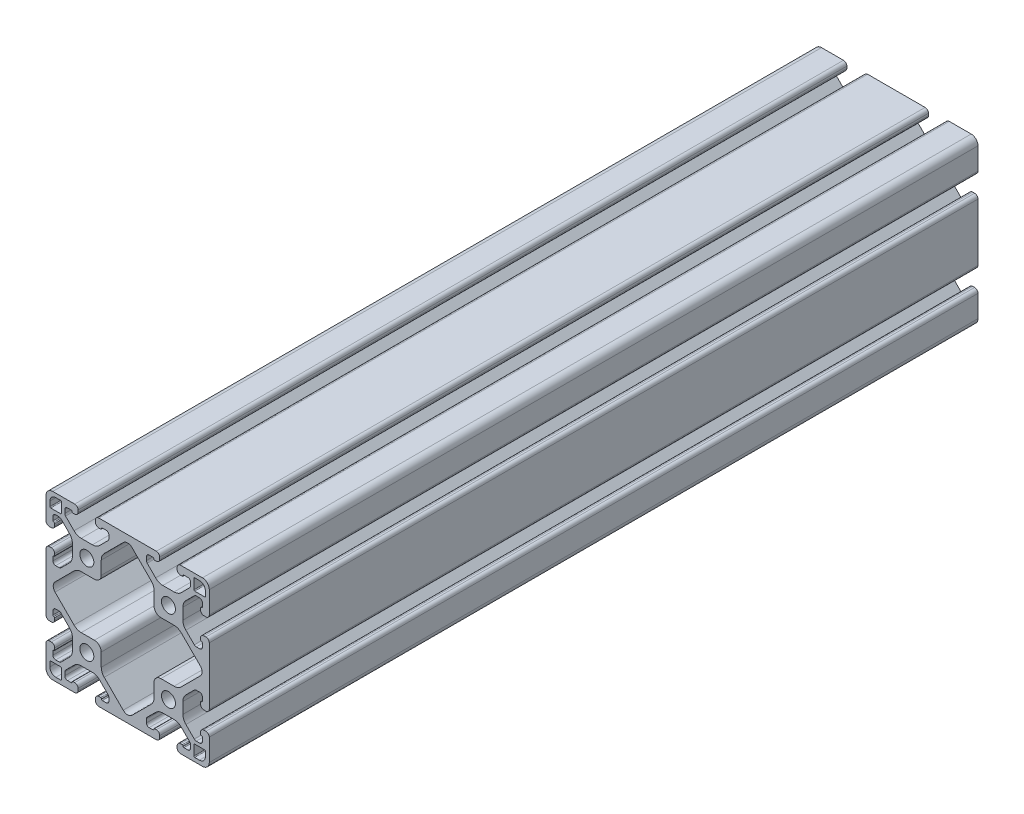
SolidWorks part; units mm, degrees
material "6061 Alloy"
ref_plane "Front Plane" through (0, 0, 0) normal (0, 0, 1) x (1, 0, 0)
ref_plane "Top Plane" through (0, 0, 0) normal (0, 1, 0) x (1, 0, 0)
ref_plane "Right Plane" through (0, 0, 0) normal (1, 0, 0) x (0, 0, -1)
sketch "Sketch1" plane through (0, 0, 0) normal (0, 0, 1) x (1, 0, 0)
  line L0 (33.8793, 2.0655) -> (25.0169, 10.9278)
  line L1 (25.0169, -10.9278) -> (33.8793, -2.0655)
  line L2 (15.494, -12.319) -> (21.6583, -12.319)
  line L3 (12.319, -21.6583) -> (12.319, -15.494)
  line L4 (2.0655, -33.8793) -> (10.9278, -25.0169)
  line L5 (-10.9278, -25.0169) -> (-2.0655, -33.8793)
  line L6 (-12.319, -15.494) -> (-12.319, -21.6583)
  line L7 (-21.6583, -12.319) -> (-15.494, -12.319)
  line L8 (-33.8793, -2.0655) -> (-25.0169, -10.9278)
  line L9 (-25.0169, 10.9278) -> (-33.8793, 2.0655)
  line L10 (-15.494, 12.319) -> (-21.6583, 12.319)
  line L11 (-12.319, 21.6583) -> (-12.319, 15.494)
  line L12 (-2.0655, 33.8793) -> (-10.9278, 25.0169)
  line L13 (10.9278, 25.0169) -> (2.0655, 33.8793)
  line L14 (12.319, 15.494) -> (12.319, 21.6583)
  line L15 (21.6583, 12.319) -> (15.494, 12.319)
  line L16 (-16.4102, 23.2956) -> (-17.6936, 22.0229) construction
  line L17 (-16.0771, 20.4064) -> (-14.8044, 21.6898) construction
  line L18 (-14.7067, 16.3231) -> (-16.0771, 17.6936) construction
  line L19 (-17.6936, 16.0771) -> (-16.3231, 14.7067) construction
  line L20 (-21.7769, 14.7067) -> (-20.4064, 16.0771) construction
  line L21 (-22.0229, 17.6936) -> (-23.3933, 16.3231) construction
  line L22 (-23.3933, 21.7769) -> (-22.0229, 20.4064) construction
  line L23 (-20.4064, 22.0229) -> (-21.7769, 23.3933) construction
  line L24 (14.8044, 21.6898) -> (16.0771, 20.4064) construction
  line L25 (17.6936, 22.0229) -> (16.4102, 23.2956) construction
  line L26 (21.7769, 23.3933) -> (20.4064, 22.0229) construction
  line L27 (22.0229, 20.4064) -> (23.3933, 21.7769) construction
  line L28 (23.3933, 16.3231) -> (22.0229, 17.6936) construction
  line L29 (20.4064, 16.0771) -> (21.7769, 14.7067) construction
  line L30 (16.3231, 14.7067) -> (17.6936, 16.0771) construction
  line L31 (16.0771, 17.6936) -> (14.7067, 16.3231) construction
  line L32 (16.4102, -23.2956) -> (17.6936, -22.0229) construction
  line L33 (16.0771, -20.4064) -> (14.8044, -21.6898) construction
  line L34 (14.7067, -16.3231) -> (16.0771, -17.6936) construction
  line L35 (17.6936, -16.0771) -> (16.3231, -14.7067) construction
  line L36 (21.7769, -14.7067) -> (20.4064, -16.0771) construction
  line L37 (22.0229, -17.6936) -> (23.3933, -16.3231) construction
  line L38 (23.3933, -21.7769) -> (22.0229, -20.4064) construction
  line L39 (20.4064, -22.0229) -> (21.7769, -23.3933) construction
  line L40 (-14.8044, -21.6898) -> (-16.0771, -20.4064) construction
  line L41 (-17.6936, -22.0229) -> (-16.4102, -23.2956) construction
  line L42 (-21.7769, -23.3933) -> (-20.4064, -22.0229) construction
  line L43 (-22.0229, -20.4064) -> (-23.3933, -21.7769) construction
  line L44 (-23.3933, -16.3231) -> (-22.0229, -17.6936) construction
  line L45 (-20.4064, -16.0771) -> (-21.7769, -14.7067) construction
  line L46 (-16.3231, -14.7067) -> (-17.6936, -16.0771) construction
  line L47 (-16.0771, -17.6936) -> (-14.7067, -16.3231) construction
  line L48 (34.417, -25.908) -> (34.4932, -25.908)
  line L49 (34.8742, -26.289) -> (34.8742, -28.067)
  line L50 (33.6042, -29.337) -> (32.0183, -29.337)
  line L51 (31.1203, -28.965) -> (27.1722, -25.0169)
  line L52 (25.781, -21.6583) -> (25.781, -16.4417)
  line L53 (27.1722, -13.0831) -> (31.1203, -9.135)
  line L54 (32.0183, -8.763) -> (33.6042, -8.763)
  line L55 (34.8742, -10.033) -> (34.8742, -11.811)
  line L56 (34.4932, -12.192) -> (34.417, -12.192)
  line L57 (34.036, -12.573) -> (34.036, -13.4112)
  line L58 (35.6108, -14.986) -> (36.5252, -14.986)
  line L59 (38.1, -13.4112) -> (38.1, 13.4112)
  line L60 (36.5252, 14.986) -> (35.6108, 14.986)
  line L61 (34.036, 13.4112) -> (34.036, 12.573)
  line L62 (34.417, 12.192) -> (34.4932, 12.192)
  line L63 (34.8742, 11.811) -> (34.8742, 10.033)
  line L64 (33.6042, 8.763) -> (32.0183, 8.763)
  line L65 (31.1203, 9.135) -> (27.1722, 13.0831)
  line L66 (25.781, 16.4417) -> (25.781, 21.6583)
  line L67 (27.1722, 25.0169) -> (31.1203, 28.965)
  line L68 (32.0183, 29.337) -> (33.6042, 29.337)
  line L69 (34.8742, 28.067) -> (34.8742, 26.289)
  line L70 (34.4932, 25.908) -> (34.417, 25.908)
  line L71 (34.036, 25.527) -> (34.036, 24.6888)
  line L72 (35.6108, 23.114) -> (36.5252, 23.114)
  line L73 (38.1, 24.6888) -> (38.1, 34.925)
  line L74 (34.925, 38.1) -> (24.6888, 38.1)
  line L75 (23.114, 36.5252) -> (23.114, 35.6108)
  line L76 (24.6888, 34.036) -> (25.527, 34.036)
  line L77 (25.908, 34.417) -> (25.908, 34.4932)
  line L78 (26.289, 34.8742) -> (28.067, 34.8742)
  line L79 (29.337, 33.6042) -> (29.337, 32.0183)
  line L80 (28.965, 31.1203) -> (25.0169, 27.1722)
  line L81 (21.6583, 25.781) -> (16.4417, 25.781)
  line L82 (13.0831, 27.1722) -> (9.135, 31.1203)
  line L83 (8.763, 32.0183) -> (8.763, 33.6042)
  line L84 (10.033, 34.8742) -> (11.811, 34.8742)
  line L85 (12.192, 34.4932) -> (12.192, 34.417)
  line L86 (12.573, 34.036) -> (13.4112, 34.036)
  line L87 (14.986, 35.6108) -> (14.986, 36.5252)
  line L88 (13.4112, 38.1) -> (-13.4112, 38.1)
  line L89 (-14.986, 36.5252) -> (-14.986, 35.6108)
  line L90 (-13.4112, 34.036) -> (-12.573, 34.036)
  line L91 (-12.192, 34.417) -> (-12.192, 34.4932)
  line L92 (-11.811, 34.8742) -> (-10.033, 34.8742)
  line L93 (-8.763, 33.6042) -> (-8.763, 32.0183)
  line L94 (-9.135, 31.1203) -> (-13.0831, 27.1722)
  line L95 (-16.4417, 25.781) -> (-21.6583, 25.781)
  line L96 (-25.0169, 27.1722) -> (-28.965, 31.1203)
  line L97 (-29.337, 32.0183) -> (-29.337, 33.6042)
  line L98 (-28.067, 34.8742) -> (-26.289, 34.8742)
  line L99 (-25.908, 34.4932) -> (-25.908, 34.417)
  line L100 (-25.527, 34.036) -> (-24.6888, 34.036)
  line L101 (-23.114, 35.6108) -> (-23.114, 36.5252)
  line L102 (-24.6888, 38.1) -> (-34.925, 38.1)
  line L103 (-38.1, 34.925) -> (-38.1, 24.6888)
  line L104 (-36.5252, 23.114) -> (-35.6108, 23.114)
  line L105 (-34.036, 24.6888) -> (-34.036, 25.527)
  line L106 (-34.417, 25.908) -> (-34.4932, 25.908)
  line L107 (-34.8742, 26.289) -> (-34.8742, 28.067)
  line L108 (-33.6042, 29.337) -> (-32.0183, 29.337)
  line L109 (-31.1203, 28.965) -> (-27.1722, 25.0169)
  line L110 (-25.781, 21.6583) -> (-25.781, 16.4417)
  line L111 (-27.1722, 13.0831) -> (-31.1203, 9.135)
  line L112 (-32.0183, 8.763) -> (-33.6042, 8.763)
  line L113 (-34.8742, 10.033) -> (-34.8742, 11.811)
  line L114 (-34.4932, 12.192) -> (-34.417, 12.192)
  line L115 (-34.036, 12.573) -> (-34.036, 13.4112)
  line L116 (-35.6108, 14.986) -> (-36.5252, 14.986)
  line L117 (-38.1, 13.4112) -> (-38.1, -13.4112)
  line L118 (-36.5252, -14.986) -> (-35.6108, -14.986)
  line L119 (-34.036, -13.4112) -> (-34.036, -12.573)
  line L120 (-34.417, -12.192) -> (-34.4932, -12.192)
  line L121 (-34.8742, -11.811) -> (-34.8742, -10.033)
  line L122 (-33.6042, -8.763) -> (-32.0183, -8.763)
  line L123 (-31.1203, -9.135) -> (-27.1722, -13.0831)
  line L124 (-25.781, -16.4417) -> (-25.781, -21.6583)
  line L125 (-27.1722, -25.0169) -> (-31.1203, -28.965)
  line L126 (-32.0183, -29.337) -> (-33.6042, -29.337)
  line L127 (-34.8742, -28.067) -> (-34.8742, -26.289)
  line L128 (-34.4932, -25.908) -> (-34.417, -25.908)
  line L129 (-34.036, -25.527) -> (-34.036, -24.6888)
  line L130 (-35.6108, -23.114) -> (-36.5252, -23.114)
  line L131 (-38.1, -24.6888) -> (-38.1, -34.925)
  line L132 (-34.925, -38.1) -> (-24.6888, -38.1)
  line L133 (-23.114, -36.5252) -> (-23.114, -35.6108)
  line L134 (-24.6888, -34.036) -> (-25.527, -34.036)
  line L135 (-25.908, -34.417) -> (-25.908, -34.4932)
  line L136 (-26.289, -34.8742) -> (-28.067, -34.8742)
  line L137 (-29.337, -33.6042) -> (-29.337, -32.0183)
  line L138 (-28.965, -31.1203) -> (-25.0169, -27.1722)
  line L139 (-21.6583, -25.781) -> (-16.4417, -25.781)
  line L140 (-13.0831, -27.1722) -> (-9.135, -31.1203)
  line L141 (-8.763, -32.0183) -> (-8.763, -33.6042)
  line L142 (-10.033, -34.8742) -> (-11.811, -34.8742)
  line L143 (-12.192, -34.4932) -> (-12.192, -34.417)
  line L144 (-12.573, -34.036) -> (-13.4112, -34.036)
  line L145 (-14.986, -35.6108) -> (-14.986, -36.5252)
  line L146 (-13.4112, -38.1) -> (13.4112, -38.1)
  line L147 (14.986, -36.5252) -> (14.986, -35.6108)
  line L148 (13.4112, -34.036) -> (12.573, -34.036)
  line L149 (12.192, -34.417) -> (12.192, -34.4932)
  line L150 (11.811, -34.8742) -> (10.033, -34.8742)
  line L151 (8.763, -33.6042) -> (8.763, -32.0183)
  line L152 (9.135, -31.1203) -> (13.0831, -27.1722)
  line L153 (16.4417, -25.781) -> (21.6583, -25.781)
  line L154 (25.0169, -27.1722) -> (28.965, -31.1203)
  line L155 (29.337, -32.0183) -> (29.337, -33.6042)
  line L156 (28.067, -34.8742) -> (26.289, -34.8742)
  line L157 (25.908, -34.4932) -> (25.908, -34.417)
  line L158 (25.527, -34.036) -> (24.6888, -34.036)
  line L159 (23.114, -35.6108) -> (23.114, -36.5252)
  line L160 (24.6888, -38.1) -> (34.925, -38.1)
  line L161 (38.1, -34.925) -> (38.1, -24.6888)
  line L162 (36.5252, -23.114) -> (35.6108, -23.114)
  line L163 (34.036, -24.6888) -> (34.036, -25.527)
  line L164 (-31.2928, 36.2966) -> (-33.5026, 36.2966)
  line L165 (-30.9118, 31.2928) -> (-30.9118, 35.9156)
  line L166 (-35.9156, 30.9118) -> (-31.2928, 30.9118)
  line L167 (-36.2966, 33.5026) -> (-36.2966, 31.2928)
  line L168 (30.9118, 35.9156) -> (30.9118, 31.2928)
  line L169 (33.5026, 36.2966) -> (31.2928, 36.2966)
  line L170 (36.2966, 31.2928) -> (36.2966, 33.5026)
  line L171 (31.2928, 30.9118) -> (35.9156, 30.9118)
  line L172 (31.2928, -36.2966) -> (33.5026, -36.2966)
  line L173 (30.9118, -31.2928) -> (30.9118, -35.9156)
  line L174 (35.9156, -30.9118) -> (31.2928, -30.9118)
  line L175 (36.2966, -33.5026) -> (36.2966, -31.2928)
  line L176 (-30.9118, -35.9156) -> (-30.9118, -31.2928)
  line L177 (-33.5026, -36.2966) -> (-31.2928, -36.2966)
  line L178 (-36.2966, -31.2928) -> (-36.2966, -33.5026)
  line L179 (-31.2928, -30.9118) -> (-35.9156, -30.9118)
  arc A0 (33.8793, -2.0655) -> (33.8793, 2.0655) centre (31.8138, 0) ccw
  arc A1 (21.6583, -12.319) -> (25.0169, -10.9278) centre (21.6583, -7.5692) ccw
  arc A2 (15.494, -12.319) -> (12.319, -15.494) centre (15.494, -15.494) ccw
  arc A3 (10.9278, -25.0169) -> (12.319, -21.6583) centre (7.5692, -21.6583) ccw
  arc A4 (-2.0655, -33.8793) -> (2.0655, -33.8793) centre (0, -31.8138) ccw
  arc A5 (-12.319, -21.6583) -> (-10.9278, -25.0169) centre (-7.5692, -21.6583) ccw
  arc A6 (-12.319, -15.494) -> (-15.494, -12.319) centre (-15.494, -15.494) ccw
  arc A7 (-25.0169, -10.9278) -> (-21.6583, -12.319) centre (-21.6583, -7.5692) ccw
  arc A8 (-33.8793, 2.0655) -> (-33.8793, -2.0655) centre (-31.8138, 0) ccw
  arc A9 (-21.6583, 12.319) -> (-25.0169, 10.9278) centre (-21.6583, 7.5692) ccw
  arc A10 (-15.494, 12.319) -> (-12.319, 15.494) centre (-15.494, 15.494) ccw
  arc A11 (-10.9278, 25.0169) -> (-12.319, 21.6583) centre (-7.5692, 21.6583) ccw
  arc A12 (2.0655, 33.8793) -> (-2.0655, 33.8793) centre (0, 31.8138) ccw
  arc A13 (12.319, 21.6583) -> (10.9278, 25.0169) centre (7.5692, 21.6583) ccw
  arc A14 (12.319, 15.494) -> (15.494, 12.319) centre (15.494, 15.494) ccw
  arc A15 (25.0169, 10.9278) -> (21.6583, 12.319) centre (21.6583, 7.5692) ccw
  arc A16 (-14.8044, 21.6898) -> (-16.4102, 23.2956) centre (-15.5149, 22.5851) ccw construction
  arc A17 (-16.0771, 17.6936) -> (-16.0771, 20.4064) centre (-19.05, 19.05) ccw construction
  arc A18 (-16.3231, 14.7067) -> (-14.7067, 16.3231) centre (-15.5149, 15.5149) ccw construction
  arc A19 (-20.4064, 16.0771) -> (-17.6936, 16.0771) centre (-19.05, 19.05) ccw construction
  arc A20 (-23.3933, 16.3231) -> (-21.7769, 14.7067) centre (-22.5851, 15.5149) ccw construction
  arc A21 (-22.0229, 20.4064) -> (-22.0229, 17.6936) centre (-19.05, 19.05) ccw construction
  arc A22 (-21.7769, 23.3933) -> (-23.3933, 21.7769) centre (-22.5851, 22.5851) ccw construction
  arc A23 (-17.6936, 22.0229) -> (-20.4064, 22.0229) centre (-19.05, 19.05) ccw construction
  arc A24 (16.0771, 20.4064) -> (16.0771, 17.6936) centre (19.05, 19.05) ccw construction
  arc A25 (16.4102, 23.2956) -> (14.8044, 21.6898) centre (15.5149, 22.5851) ccw construction
  arc A26 (20.4064, 22.0229) -> (17.6936, 22.0229) centre (19.05, 19.05) ccw construction
  arc A27 (23.3933, 21.7769) -> (21.7769, 23.3933) centre (22.5851, 22.5851) ccw construction
  arc A28 (22.0229, 17.6936) -> (22.0229, 20.4064) centre (19.05, 19.05) ccw construction
  arc A29 (21.7769, 14.7067) -> (23.3933, 16.3231) centre (22.5851, 15.5149) ccw construction
  arc A30 (17.6936, 16.0771) -> (20.4064, 16.0771) centre (19.05, 19.05) ccw construction
  arc A31 (14.7067, 16.3231) -> (16.3231, 14.7067) centre (15.5149, 15.5149) ccw construction
  arc A32 (17.6936, -22.0229) -> (20.4064, -22.0229) centre (19.05, -19.05) ccw construction
  arc A33 (14.8044, -21.6898) -> (16.4102, -23.2956) centre (15.5149, -22.5851) ccw construction
  arc A34 (16.0771, -17.6936) -> (16.0771, -20.4064) centre (19.05, -19.05) ccw construction
  arc A35 (16.3231, -14.7067) -> (14.7067, -16.3231) centre (15.5149, -15.5149) ccw construction
  arc A36 (20.4064, -16.0771) -> (17.6936, -16.0771) centre (19.05, -19.05) ccw construction
  arc A37 (23.3933, -16.3231) -> (21.7769, -14.7067) centre (22.5851, -15.5149) ccw construction
  arc A38 (22.0229, -20.4064) -> (22.0229, -17.6936) centre (19.05, -19.05) ccw construction
  arc A39 (21.7769, -23.3933) -> (23.3933, -21.7769) centre (22.5851, -22.5851) ccw construction
  arc A40 (-16.4102, -23.2956) -> (-14.8044, -21.6898) centre (-15.5149, -22.5851) ccw construction
  arc A41 (-20.4064, -22.0229) -> (-17.6936, -22.0229) centre (-19.05, -19.05) ccw construction
  arc A42 (-23.3933, -21.7769) -> (-21.7769, -23.3933) centre (-22.5851, -22.5851) ccw construction
  arc A43 (-22.0229, -17.6936) -> (-22.0229, -20.4064) centre (-19.05, -19.05) ccw construction
  arc A44 (-21.7769, -14.7067) -> (-23.3933, -16.3231) centre (-22.5851, -15.5149) ccw construction
  arc A45 (-17.6936, -16.0771) -> (-20.4064, -16.0771) centre (-19.05, -19.05) ccw construction
  arc A46 (-14.7067, -16.3231) -> (-16.3231, -14.7067) centre (-15.5149, -15.5149) ccw construction
  arc A47 (-16.0771, -20.4064) -> (-16.0771, -17.6936) centre (-19.05, -19.05) ccw construction
  arc A48 (34.036, -25.527) -> (34.417, -25.908) centre (34.417, -25.527) ccw
  arc A49 (34.8742, -26.289) -> (34.4932, -25.908) centre (34.4932, -26.289) ccw
  arc A50 (33.6042, -29.337) -> (34.8742, -28.067) centre (33.6042, -28.067) ccw
  arc A51 (31.1203, -28.965) -> (32.0183, -29.337) centre (32.0183, -28.067) ccw
  arc A52 (25.781, -21.6583) -> (27.1722, -25.0169) centre (30.5308, -21.6583) ccw
  arc A53 (27.1722, -13.0831) -> (25.781, -16.4417) centre (30.5308, -16.4417) ccw
  arc A54 (32.0183, -8.763) -> (31.1203, -9.135) centre (32.0183, -10.033) ccw
  arc A55 (34.8742, -10.033) -> (33.6042, -8.763) centre (33.6042, -10.033) ccw
  arc A56 (34.4932, -12.192) -> (34.8742, -11.811) centre (34.4932, -11.811) ccw
  arc A57 (34.417, -12.192) -> (34.036, -12.573) centre (34.417, -12.573) ccw
  arc A58 (34.036, -13.4112) -> (35.6108, -14.986) centre (35.6108, -13.4112) ccw
  arc A59 (36.5252, -14.986) -> (38.1, -13.4112) centre (36.5252, -13.4112) ccw
  arc A60 (38.1, 13.4112) -> (36.5252, 14.986) centre (36.5252, 13.4112) ccw
  arc A61 (35.6108, 14.986) -> (34.036, 13.4112) centre (35.6108, 13.4112) ccw
  arc A62 (34.036, 12.573) -> (34.417, 12.192) centre (34.417, 12.573) ccw
  arc A63 (34.8742, 11.811) -> (34.4932, 12.192) centre (34.4932, 11.811) ccw
  arc A64 (33.6042, 8.763) -> (34.8742, 10.033) centre (33.6042, 10.033) ccw
  arc A65 (31.1203, 9.135) -> (32.0183, 8.763) centre (32.0183, 10.033) ccw
  arc A66 (25.781, 16.4417) -> (27.1722, 13.0831) centre (30.5308, 16.4417) ccw
  arc A67 (27.1722, 25.0169) -> (25.781, 21.6583) centre (30.5308, 21.6583) ccw
  arc A68 (32.0183, 29.337) -> (31.1203, 28.965) centre (32.0183, 28.067) ccw
  arc A69 (34.8742, 28.067) -> (33.6042, 29.337) centre (33.6042, 28.067) ccw
  arc A70 (34.4932, 25.908) -> (34.8742, 26.289) centre (34.4932, 26.289) ccw
  arc A71 (34.417, 25.908) -> (34.036, 25.527) centre (34.417, 25.527) ccw
  arc A72 (34.036, 24.6888) -> (35.6108, 23.114) centre (35.6108, 24.6888) ccw
  arc A73 (36.5252, 23.114) -> (38.1, 24.6888) centre (36.5252, 24.6888) ccw
  arc A74 (38.1, 34.925) -> (34.925, 38.1) centre (34.925, 34.925) ccw
  arc A75 (24.6888, 38.1) -> (23.114, 36.5252) centre (24.6888, 36.5252) ccw
  arc A76 (23.114, 35.6108) -> (24.6888, 34.036) centre (24.6888, 35.6108) ccw
  arc A77 (25.527, 34.036) -> (25.908, 34.417) centre (25.527, 34.417) ccw
  arc A78 (26.289, 34.8742) -> (25.908, 34.4932) centre (26.289, 34.4932) ccw
  arc A79 (29.337, 33.6042) -> (28.067, 34.8742) centre (28.067, 33.6042) ccw
  arc A80 (28.965, 31.1203) -> (29.337, 32.0183) centre (28.067, 32.0183) ccw
  arc A81 (21.6583, 25.781) -> (25.0169, 27.1722) centre (21.6583, 30.5308) ccw
  arc A82 (13.0831, 27.1722) -> (16.4417, 25.781) centre (16.4417, 30.5308) ccw
  arc A83 (8.763, 32.0183) -> (9.135, 31.1203) centre (10.033, 32.0183) ccw
  arc A84 (10.033, 34.8742) -> (8.763, 33.6042) centre (10.033, 33.6042) ccw
  arc A85 (12.192, 34.4932) -> (11.811, 34.8742) centre (11.811, 34.4932) ccw
  arc A86 (12.192, 34.417) -> (12.573, 34.036) centre (12.573, 34.417) ccw
  arc A87 (13.4112, 34.036) -> (14.986, 35.6108) centre (13.4112, 35.6108) ccw
  arc A88 (14.986, 36.5252) -> (13.4112, 38.1) centre (13.4112, 36.5252) ccw
  arc A89 (-13.4112, 38.1) -> (-14.986, 36.5252) centre (-13.4112, 36.5252) ccw
  arc A90 (-14.986, 35.6108) -> (-13.4112, 34.036) centre (-13.4112, 35.6108) ccw
  arc A91 (-12.573, 34.036) -> (-12.192, 34.417) centre (-12.573, 34.417) ccw
  arc A92 (-11.811, 34.8742) -> (-12.192, 34.4932) centre (-11.811, 34.4932) ccw
  arc A93 (-8.763, 33.6042) -> (-10.033, 34.8742) centre (-10.033, 33.6042) ccw
  arc A94 (-9.135, 31.1203) -> (-8.763, 32.0183) centre (-10.033, 32.0183) ccw
  arc A95 (-16.4417, 25.781) -> (-13.0831, 27.1722) centre (-16.4417, 30.5308) ccw
  arc A96 (-25.0169, 27.1722) -> (-21.6583, 25.781) centre (-21.6583, 30.5308) ccw
  arc A97 (-29.337, 32.0183) -> (-28.965, 31.1203) centre (-28.067, 32.0183) ccw
  arc A98 (-28.067, 34.8742) -> (-29.337, 33.6042) centre (-28.067, 33.6042) ccw
  arc A99 (-25.908, 34.4932) -> (-26.289, 34.8742) centre (-26.289, 34.4932) ccw
  arc A100 (-25.908, 34.417) -> (-25.527, 34.036) centre (-25.527, 34.417) ccw
  arc A101 (-24.6888, 34.036) -> (-23.114, 35.6108) centre (-24.6888, 35.6108) ccw
  arc A102 (-23.114, 36.5252) -> (-24.6888, 38.1) centre (-24.6888, 36.5252) ccw
  arc A103 (-34.925, 38.1) -> (-38.1, 34.925) centre (-34.925, 34.925) ccw
  arc A104 (-38.1, 24.6888) -> (-36.5252, 23.114) centre (-36.5252, 24.6888) ccw
  arc A105 (-35.6108, 23.114) -> (-34.036, 24.6888) centre (-35.6108, 24.6888) ccw
  arc A106 (-34.036, 25.527) -> (-34.417, 25.908) centre (-34.417, 25.527) ccw
  arc A107 (-34.8742, 26.289) -> (-34.4932, 25.908) centre (-34.4932, 26.289) ccw
  arc A108 (-33.6042, 29.337) -> (-34.8742, 28.067) centre (-33.6042, 28.067) ccw
  arc A109 (-31.1203, 28.965) -> (-32.0183, 29.337) centre (-32.0183, 28.067) ccw
  arc A110 (-25.781, 21.6583) -> (-27.1722, 25.0169) centre (-30.5308, 21.6583) ccw
  arc A111 (-27.1722, 13.0831) -> (-25.781, 16.4417) centre (-30.5308, 16.4417) ccw
  arc A112 (-32.0183, 8.763) -> (-31.1203, 9.135) centre (-32.0183, 10.033) ccw
  arc A113 (-34.8742, 10.033) -> (-33.6042, 8.763) centre (-33.6042, 10.033) ccw
  arc A114 (-34.4932, 12.192) -> (-34.8742, 11.811) centre (-34.4932, 11.811) ccw
  arc A115 (-34.417, 12.192) -> (-34.036, 12.573) centre (-34.417, 12.573) ccw
  arc A116 (-34.036, 13.4112) -> (-35.6108, 14.986) centre (-35.6108, 13.4112) ccw
  arc A117 (-36.5252, 14.986) -> (-38.1, 13.4112) centre (-36.5252, 13.4112) ccw
  arc A118 (-38.1, -13.4112) -> (-36.5252, -14.986) centre (-36.5252, -13.4112) ccw
  arc A119 (-35.6108, -14.986) -> (-34.036, -13.4112) centre (-35.6108, -13.4112) ccw
  arc A120 (-34.036, -12.573) -> (-34.417, -12.192) centre (-34.417, -12.573) ccw
  arc A121 (-34.8742, -11.811) -> (-34.4932, -12.192) centre (-34.4932, -11.811) ccw
  arc A122 (-33.6042, -8.763) -> (-34.8742, -10.033) centre (-33.6042, -10.033) ccw
  arc A123 (-31.1203, -9.135) -> (-32.0183, -8.763) centre (-32.0183, -10.033) ccw
  arc A124 (-25.781, -16.4417) -> (-27.1722, -13.0831) centre (-30.5308, -16.4417) ccw
  arc A125 (-27.1722, -25.0169) -> (-25.781, -21.6583) centre (-30.5308, -21.6583) ccw
  arc A126 (-32.0183, -29.337) -> (-31.1203, -28.965) centre (-32.0183, -28.067) ccw
  arc A127 (-34.8742, -28.067) -> (-33.6042, -29.337) centre (-33.6042, -28.067) ccw
  arc A128 (-34.4932, -25.908) -> (-34.8742, -26.289) centre (-34.4932, -26.289) ccw
  arc A129 (-34.417, -25.908) -> (-34.036, -25.527) centre (-34.417, -25.527) ccw
  arc A130 (-34.036, -24.6888) -> (-35.6108, -23.114) centre (-35.6108, -24.6888) ccw
  arc A131 (-36.5252, -23.114) -> (-38.1, -24.6888) centre (-36.5252, -24.6888) ccw
  arc A132 (-38.1, -34.925) -> (-34.925, -38.1) centre (-34.925, -34.925) ccw
  arc A133 (-24.6888, -38.1) -> (-23.114, -36.5252) centre (-24.6888, -36.5252) ccw
  arc A134 (-23.114, -35.6108) -> (-24.6888, -34.036) centre (-24.6888, -35.6108) ccw
  arc A135 (-25.527, -34.036) -> (-25.908, -34.417) centre (-25.527, -34.417) ccw
  arc A136 (-26.289, -34.8742) -> (-25.908, -34.4932) centre (-26.289, -34.4932) ccw
  arc A137 (-29.337, -33.6042) -> (-28.067, -34.8742) centre (-28.067, -33.6042) ccw
  arc A138 (-28.965, -31.1203) -> (-29.337, -32.0183) centre (-28.067, -32.0183) ccw
  arc A139 (-21.6583, -25.781) -> (-25.0169, -27.1722) centre (-21.6583, -30.5308) ccw
  arc A140 (-13.0831, -27.1722) -> (-16.4417, -25.781) centre (-16.4417, -30.5308) ccw
  arc A141 (-8.763, -32.0183) -> (-9.135, -31.1203) centre (-10.033, -32.0183) ccw
  arc A142 (-10.033, -34.8742) -> (-8.763, -33.6042) centre (-10.033, -33.6042) ccw
  arc A143 (-12.192, -34.4932) -> (-11.811, -34.8742) centre (-11.811, -34.4932) ccw
  arc A144 (-12.192, -34.417) -> (-12.573, -34.036) centre (-12.573, -34.417) ccw
  arc A145 (-13.4112, -34.036) -> (-14.986, -35.6108) centre (-13.4112, -35.6108) ccw
  arc A146 (-14.986, -36.5252) -> (-13.4112, -38.1) centre (-13.4112, -36.5252) ccw
  arc A147 (13.4112, -38.1) -> (14.986, -36.5252) centre (13.4112, -36.5252) ccw
  arc A148 (14.986, -35.6108) -> (13.4112, -34.036) centre (13.4112, -35.6108) ccw
  arc A149 (12.573, -34.036) -> (12.192, -34.417) centre (12.573, -34.417) ccw
  arc A150 (11.811, -34.8742) -> (12.192, -34.4932) centre (11.811, -34.4932) ccw
  arc A151 (8.763, -33.6042) -> (10.033, -34.8742) centre (10.033, -33.6042) ccw
  arc A152 (9.135, -31.1203) -> (8.763, -32.0183) centre (10.033, -32.0183) ccw
  arc A153 (16.4417, -25.781) -> (13.0831, -27.1722) centre (16.4417, -30.5308) ccw
  arc A154 (25.0169, -27.1722) -> (21.6583, -25.781) centre (21.6583, -30.5308) ccw
  arc A155 (29.337, -32.0183) -> (28.965, -31.1203) centre (28.067, -32.0183) ccw
  arc A156 (28.067, -34.8742) -> (29.337, -33.6042) centre (28.067, -33.6042) ccw
  arc A157 (25.908, -34.4932) -> (26.289, -34.8742) centre (26.289, -34.4932) ccw
  arc A158 (25.908, -34.417) -> (25.527, -34.036) centre (25.527, -34.417) ccw
  arc A159 (24.6888, -34.036) -> (23.114, -35.6108) centre (24.6888, -35.6108) ccw
  arc A160 (23.114, -36.5252) -> (24.6888, -38.1) centre (24.6888, -36.5252) ccw
  arc A161 (34.925, -38.1) -> (38.1, -34.925) centre (34.925, -34.925) ccw
  arc A162 (38.1, -24.6888) -> (36.5252, -23.114) centre (36.5252, -24.6888) ccw
  arc A163 (35.6108, -23.114) -> (34.036, -24.6888) centre (35.6108, -24.6888) ccw
  circle A164 centre (-19.05, 19.05) radius 3.2677
  circle A165 centre (19.05, 19.05) radius 3.2677
  circle A166 centre (19.05, -19.05) radius 3.2677
  circle A167 centre (-19.05, -19.05) radius 3.2677
  arc A168 (-33.5026, 36.2966) -> (-36.2966, 33.5026) centre (-33.5026, 33.5026) ccw
  arc A169 (-30.9118, 35.9156) -> (-31.2928, 36.2966) centre (-31.2928, 35.9156) ccw
  arc A170 (-31.2928, 30.9118) -> (-30.9118, 31.2928) centre (-31.2928, 31.2928) ccw
  arc A171 (-36.2966, 31.2928) -> (-35.9156, 30.9118) centre (-35.9156, 31.2928) ccw
  arc A172 (30.9118, 31.2928) -> (31.2928, 30.9118) centre (31.2928, 31.2928) ccw
  arc A173 (31.2928, 36.2966) -> (30.9118, 35.9156) centre (31.2928, 35.9156) ccw
  arc A174 (36.2966, 33.5026) -> (33.5026, 36.2966) centre (33.5026, 33.5026) ccw
  arc A175 (35.9156, 30.9118) -> (36.2966, 31.2928) centre (35.9156, 31.2928) ccw
  arc A176 (33.5026, -36.2966) -> (36.2966, -33.5026) centre (33.5026, -33.5026) ccw
  arc A177 (30.9118, -35.9156) -> (31.2928, -36.2966) centre (31.2928, -35.9156) ccw
  arc A178 (31.2928, -30.9118) -> (30.9118, -31.2928) centre (31.2928, -31.2928) ccw
  arc A179 (36.2966, -31.2928) -> (35.9156, -30.9118) centre (35.9156, -31.2928) ccw
  arc A180 (-30.9118, -31.2928) -> (-31.2928, -30.9118) centre (-31.2928, -31.2928) ccw
  arc A181 (-31.2928, -36.2966) -> (-30.9118, -35.9156) centre (-31.2928, -35.9156) ccw
  arc A182 (-36.2966, -33.5026) -> (-33.5026, -36.2966) centre (-33.5026, -33.5026) ccw
  arc A183 (-35.9156, -30.9118) -> (-36.2966, -31.2928) centre (-35.9156, -31.2928) ccw
extrude "Boss-Extrude1" add sketch "Sketch1" along normal mid plane 358.775
